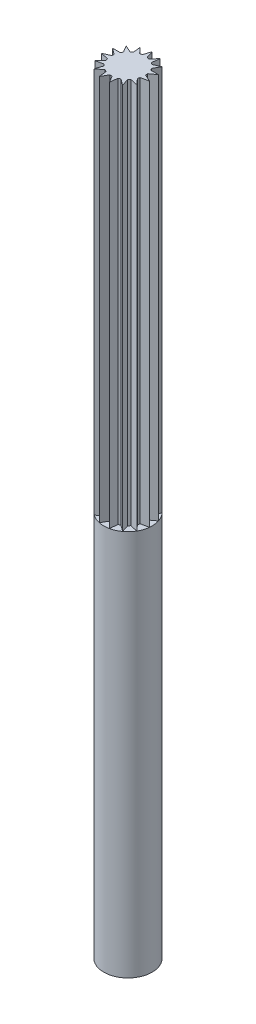
SolidWorks part; units mm, degrees
ref_plane "Front Plane" through (0, 0, 0) normal (0, 0, 1) x (1, 0, 0)
ref_plane "Top Plane" through (0, 0, 0) normal (0, 1, 0) x (1, 0, 0)
ref_plane "Right Plane" through (0, 0, 0) normal (1, 0, 0) x (0, 0, -1)
sketch "Sketch1" plane through (0, 0, 0) normal (0, 0, 1) x (1, 0, 0)
  line L0 (0, 80) -> (0, -80) construction
  line L1 (-5, -80) -> (-5, 0)
  line L2 (-5, 0) -> (0, 0)
  line L3 (0, 0) -> (0, -80)
  line L4 (0, -80) -> (-5, -80)
  dimension "D1" = 160
  dimension "D2" = 5
revolve "Revolve1" add sketch "Sketch1" angle 360 about L0
sketch "Sketch2" plane through (0, 0, 0) normal (0, 1, 0) x (1, 0, 0)
  line L0 (0, 3.5) -> (0, 5) construction
  line L3 (-0.5, 3.4641) -> (0, 5)
  line L4 (0, 5) -> (0.5, 3.4641)
  line L7 (2.0337, 4.5677) -> (1.8657, 2.9612)
  line L8 (0.9522, 3.368) -> (2.0337, 4.5677)
  line L10 (3.7157, 3.3457) -> (2.9089, 1.9464)
  line L11 (2.2398, 2.6895) -> (3.7157, 3.3457)
  line L13 (4.7553, 1.5451) -> (3.4491, 0.5949)
  line L14 (3.14, 1.546) -> (4.7553, 1.5451)
  line L16 (4.9726, -0.5226) -> (3.3929, -0.8594)
  line L17 (3.4974, 0.1352) -> (4.9726, -0.5226)
  line L19 (4.3301, -2.5) -> (2.75, -2.1651)
  line L20 (3.25, -1.299) -> (4.3301, -2.5)
  line L22 (2.9389, -4.0451) -> (1.6316, -3.0964)
  line L23 (2.4407, -2.5086) -> (2.9389, -4.0451)
  line L25 (1.0396, -4.8907) -> (0.2312, -3.4924)
  line L26 (1.2093, -3.2844) -> (1.0396, -4.8907)
  line L28 (-1.0396, -4.8907) -> (-1.2093, -3.2844)
  line L29 (-0.2312, -3.4924) -> (-1.0396, -4.8907)
  line L31 (-2.9389, -4.0451) -> (-2.4407, -2.5086)
  line L32 (-1.6316, -3.0964) -> (-2.9389, -4.0451)
  line L34 (-4.3301, -2.5) -> (-3.25, -1.299)
  line L35 (-2.75, -2.1651) -> (-4.3301, -2.5)
  line L37 (-4.9726, -0.5226) -> (-3.4974, 0.1352)
  line L38 (-3.3929, -0.8594) -> (-4.9726, -0.5226)
  line L40 (-4.7553, 1.5451) -> (-3.14, 1.546)
  line L41 (-3.4491, 0.5949) -> (-4.7553, 1.5451)
  line L43 (-3.7157, 3.3457) -> (-2.2398, 2.6895)
  line L44 (-2.9089, 1.9464) -> (-3.7157, 3.3457)
  line L46 (-2.0337, 4.5677) -> (-0.9522, 3.368)
  line L47 (-1.8657, 2.9612) -> (-2.0337, 4.5677)
  arc A0 (-2.9089, 1.9464) -> (-3.14, 1.546) centre (0, 0) ccw
  circle A1 centre (0, 0) radius 5 construction
  arc A2 (-1.8657, 2.9612) -> (-2.2398, 2.6895) centre (0, 0) ccw
  arc A3 (-0.5, 3.4641) -> (-0.9522, 3.368) centre (0, 0) ccw
  arc A4 (0.9522, 3.368) -> (0.5, 3.4641) centre (0, 0) ccw
  arc A5 (2.2398, 2.6895) -> (1.8657, 2.9612) centre (0, 0) ccw
  arc A6 (-3.4491, 0.5949) -> (-3.4974, 0.1352) centre (0, 0) ccw
  arc A7 (-3.3929, -0.8594) -> (-3.25, -1.299) centre (0, 0) ccw
  arc A8 (-2.75, -2.1651) -> (-2.4407, -2.5086) centre (0, 0) ccw
  arc A9 (-1.6316, -3.0964) -> (-1.2093, -3.2844) centre (0, 0) ccw
  arc A10 (-0.2312, -3.4924) -> (0.2312, -3.4924) centre (0, 0) ccw
  arc A11 (1.2093, -3.2844) -> (1.6316, -3.0964) centre (0, 0) ccw
  arc A12 (2.4407, -2.5086) -> (2.75, -2.1651) centre (0, 0) ccw
  arc A13 (3.25, -1.299) -> (3.3929, -0.8594) centre (0, 0) ccw
  arc A14 (3.4974, 0.1352) -> (3.4491, 0.5949) centre (0, 0) ccw
  arc A15 (3.14, 1.546) -> (2.9089, 1.9464) centre (0, 0) ccw
  point P55 (0, 0)
  dimension "D1" = 7
  dimension "D2" = 1.6152
  dimension "D3" = 15
  dimension "D4" = 1.6152
extrude "Boss-Extrude1" add sketch "Sketch2" along normal blind 80 contours A3 L46 L47 A2 L43 L44 A0 L40 L41 A6 L37 L38 A7 L34 L35 A8 L31 L32 A9 L28 L29 A10 L25 L26 A11 L22 L23 A12 L19 L20 A13 L16 L17 A14 L13 L14 A15 L10 L11 A5 L7 L8 A4 L4 L3
